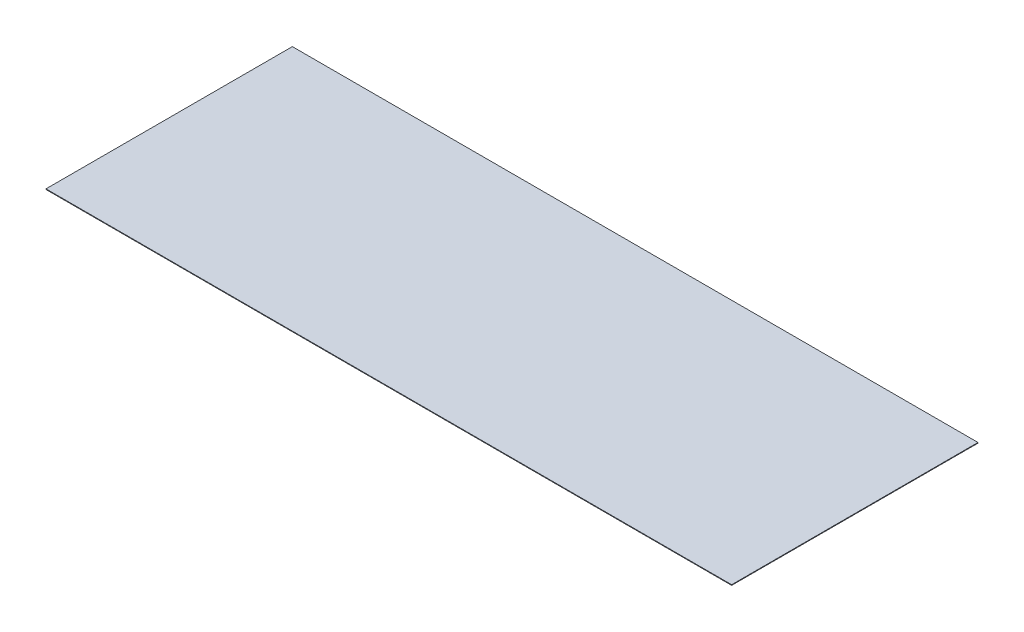
SolidWorks part; units mm, degrees
ref_plane "Front Plane" through (0, 0, 0) normal (0, 0, 1) x (1, 0, 0)
ref_plane "Top Plane" through (0, 0, 0) normal (0, 1, 0) x (1, 0, 0)
ref_plane "Right Plane" through (0, 0, 0) normal (1, 0, 0) x (0, 0, -1)
sketch "Sketch1" plane through (0, 0, 0) normal (0, 1, 0) x (1, 0, 0)
  line L1 (56.5, -20.3) -> (-56.5, -20.3)
  line L2 (56.5, -20.3) -> (56.5, 20.3)
  line L3 (56.5, 20.3) -> (-56.5, 20.3)
  line L4 (-56.5, -20.3) -> (-56.5, 20.3)
  line L5 (56.5, -20.3) -> (-56.5, 20.3) construction
  line L6 (56.5, 20.3) -> (-56.5, -20.3) construction
  point P0 (0, 0)
  dimension "D1" = 113
  dimension "D2" = 40.6
extrude "Boss-Extrude1" add sketch "Sketch1" along normal blind 0.1
